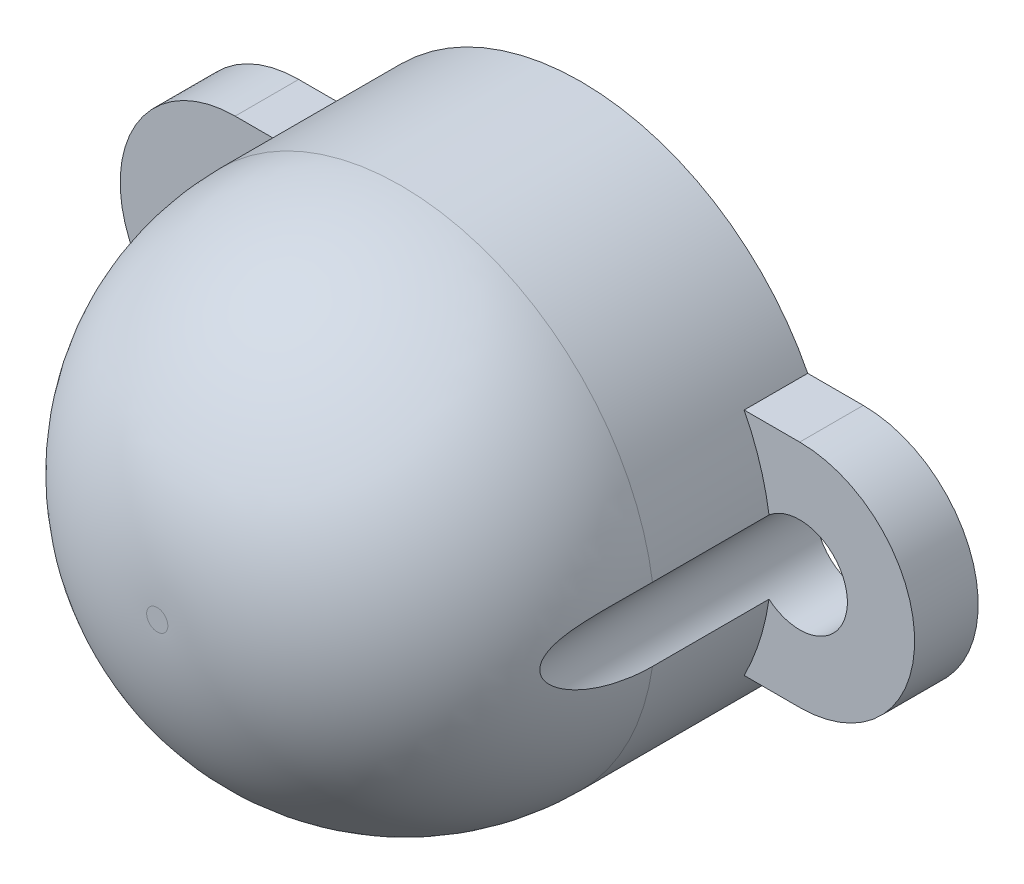
SolidWorks part; units mm, degrees
ref_plane "Front Plane" through (0, 0, 0) normal (0, 0, 1) x (1, 0, 0)
ref_plane "Top Plane" through (0, 0, 0) normal (0, 1, 0) x (1, 0, 0)
ref_plane "Right Plane" through (0, 0, 0) normal (1, 0, 0) x (0, 0, -1)
sketch "Sketch1" plane through (0, 0, 0) normal (0, 0, 1) x (1, 0, 0)
  line L0 (6.7691, 0) -> (-6.7691, 0) construction
  line L1 (6.7691, -2.7559) -> (-6.7691, -2.7559)
  line L2 (6.7691, 2.7559) -> (-6.7691, 2.7559)
  arc A0 (6.7691, -2.7559) -> (6.7691, 2.7559) centre (6.7691, 0) ccw
  arc A1 (-6.7691, 2.7559) -> (-6.7691, -2.7559) centre (-6.7691, 0) ccw
  point P2 (0, 0)
  point P8 (-9.525, 0)
  point P9 (9.525, 0)
  dimension "D1" = 19.05
  dimension "D2" = 13.5382
extrude "Boss-Extrude1" add sketch "Sketch1" along normal blind 1.524
sketch "Sketch2" plane through (0, 0, 0) normal (0, 1, 0) x (1, 0, 0)
  line L1 (0, 0) -> (6.096, 0)
  line L2 (0, 0) -> (0, -10.16)
  line L3 (0, -10.16) -> (0.254, -10.16)
  line L4 (6.096, 0) -> (6.096, -4.318)
  arc A0 (0.254, -10.16) -> (6.096, -4.318) centre (0.254, -4.318) ccw
  dimension "D2" = 5.842
  dimension "D1" = 6.096
  dimension "D3" = 10.16
sketch "Sketch4" plane through (0, 0, 0) normal (0, 0, 1) x (1, 0, 0)
  line L0 (6.7691, 0) -> (-6.7691, 0) construction
  line L1 (6.7691, -2.7559) -> (-6.7691, -2.7559)
  line L2 (6.7691, 2.7559) -> (-6.7691, 2.7559)
  arc A0 (6.7691, -2.7559) -> (6.7691, 2.7559) centre (6.7691, 0) ccw
  arc A1 (-6.7691, 2.7559) -> (-6.7691, -2.7559) centre (-6.7691, 0) ccw
  circle A2 centre (-6.7691, 0) radius 1.143
  circle A3 centre (6.7691, 0) radius 1.143
  point P2 (0, 0)
  point P8 (-9.525, 0)
  point P9 (9.525, 0)
  dimension "D3" = 2.286
  dimension "D1" = 19.05
  dimension "D2" = 13.5382
revolve "Revolve2" add sketch "Sketch2" angle 360 about L2
extrude "Cut-Extrude6" cut sketch "Sketch4" along normal blind 28.702 contours A2 | A3
equation "\"1n\"=1.13"
